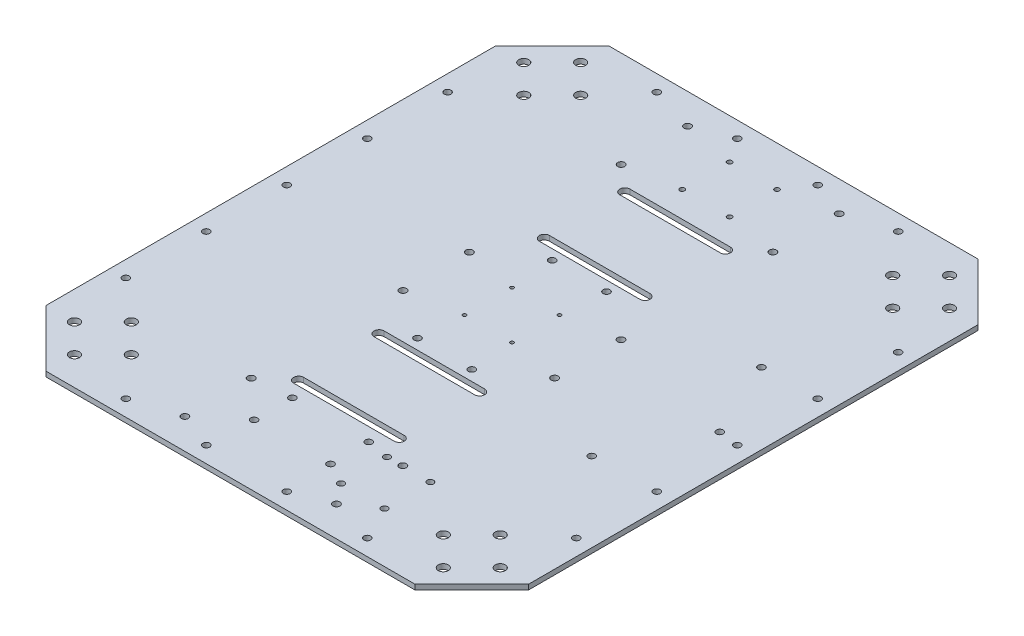
SolidWorks part; units mm, degrees
ref_plane "Front Plane" through (0, 0, 0) normal (0, 0, 1) x (1, 0, 0)
ref_plane "Top Plane" through (0, 0, 0) normal (0, 1, 0) x (1, 0, 0)
ref_plane "Right Plane" through (0, 0, 0) normal (1, 0, 0) x (0, 0, -1)
sketch "Sketch1" plane through (0, 0, 0) normal (0, 1, 0) x (1, 0, 0)
  line L0 (-121.2861, 87.138) -> (-85.365, 123.059)
  line L1 (-121.2861, 123.059) -> (183.5139, 123.059)
  line L2 (-121.2861, 123.059) -> (-121.2861, -232.541)
  line L3 (-121.2861, -232.541) -> (183.5139, -232.541)
  line L4 (183.5139, 123.059) -> (183.5139, -232.541)
  line L5 (31.1139, 95.069) -> (31.1139, -294.9418) construction
  line L6 (-146.0448, -54.741) -> (218.038, -54.741) construction
  line L7 (183.5139, 87.138) -> (147.5929, 123.059)
  line L8 (183.5139, -196.62) -> (147.5929, -232.541)
  line L9 (-121.2861, -196.62) -> (-85.365, -232.541)
  circle A0 centre (-16.7651, 104.009) radius 2.2225
  circle A1 centre (78.9929, 104.009) radius 2.2225
  circle A2 centre (-16.7651, 62.099) radius 2.2225
  circle A3 centre (78.9929, 62.099) radius 2.2225
  circle A4 centre (-16.7651, -171.581) radius 2.2225
  circle A5 centre (78.9929, -171.581) radius 2.2225
  circle A6 centre (78.9929, -213.491) radius 2.2225
  circle A7 centre (-16.7651, -213.491) radius 2.2225
  circle A8 centre (-16.7651, -33.786) radius 2.2225
  circle A9 centre (78.9929, -33.786) radius 2.2225
  circle A10 centre (78.9929, -75.696) radius 2.2225
  circle A11 centre (-16.7651, -75.696) radius 2.2225
  point P8 (31.1139, 123.059)
  point P11 (-121.2861, -54.741)
  dimension "D6" = 95.758
  dimension "D13" = 4.445
  dimension "D1" = 304.8
  dimension "D2" = 355.6
  dimension "D3" = 45
  dimension "D4" = 50.8
  dimension "D5" = 41.91
  dimension "D7" = 104.521
  dimension "D8" = 19.05
  dimension "D9" = 41.91
  dimension "D10" = 20.955
  dimension "D11" = 95.758
  dimension "D12" = 47.879
extrude "Boss-Extrude1" add sketch "Sketch1" along normal blind 3.175
sketch "Sketch2" plane through (0, 3.175, 0) normal (0, 1, 0) x (1, 0, 0)
  line L0 (31.1139, 123.059) -> (31.1139, -287.8465) construction
  line L1 (-85.365, 123.059) -> (147.5929, 123.059) construction
  line L2 (183.5139, -54.741) -> (-158.2106, -54.741) construction
  line L3 (183.5139, 87.138) -> (183.5139, -196.62) construction
  circle A0 centre (13.8419, -12.069) radius 2.159
  circle A1 centre (48.1319, -12.069) radius 2.159
  circle A2 centre (13.8419, -97.159) radius 2.159
  circle A3 centre (48.1319, -97.159) radius 2.159
  dimension "D5" = 4.318
  dimension "D6" = 4.318
  dimension "D7" = 4.318
  dimension "D8" = 4.318
  dimension "D1" = 17.272
  dimension "D2" = 34.29
  dimension "D3" = 85.09
  dimension "D4" = 42.672
extrude "Cut-Extrude1" cut sketch "Sketch2" against normal through all
sketch "Sketch4" plane through (0, 3.175, 0) normal (0, 1, 0) x (1, 0, 0)
  line L0 (-0.6361, 48.256) -> (62.8639, 48.256) construction
  line L1 (-0.6361, 51.431) -> (62.8639, 51.431)
  line L2 (-0.6361, 45.081) -> (62.8639, 45.081)
  line L3 (-0.6361, -2.544) -> (62.8639, -2.544) construction
  line L4 (-0.6361, 0.631) -> (62.8639, 0.631)
  line L5 (-0.6361, -5.719) -> (62.8639, -5.719)
  line L6 (31.1139, 123.059) -> (31.1139, -75.2432) construction
  line L7 (-85.365, 123.059) -> (147.5929, 123.059) construction
  line L8 (-121.2861, -54.741) -> (257.7387, -54.741) construction
  line L9 (-121.2861, 87.138) -> (-121.2861, -196.62) construction
  line L10 (31.1139, -232.541) -> (31.1139, -34.2388) construction
  line L11 (-0.6361, -106.938) -> (62.8639, -106.938) construction
  line L12 (-0.6361, -110.113) -> (62.8639, -110.113)
  line L13 (-0.6361, -103.763) -> (62.8639, -103.763)
  line L14 (-0.6361, -157.738) -> (62.8639, -157.738) construction
  line L15 (-0.6361, -160.913) -> (62.8639, -160.913)
  line L16 (-0.6361, -154.563) -> (62.8639, -154.563)
  arc A0 (-0.6361, 51.431) -> (-0.6361, 45.081) centre (-0.6361, 48.256) ccw
  arc A1 (62.8639, 45.081) -> (62.8639, 51.431) centre (62.8639, 48.256) ccw
  arc A2 (-0.6361, 0.631) -> (-0.6361, -5.719) centre (-0.6361, -2.544) ccw
  arc A3 (62.8639, -5.719) -> (62.8639, 0.631) centre (62.8639, -2.544) ccw
  circle A4 centre (48.1319, -12.069) radius 2.159 construction
  arc A5 (-0.6361, -110.113) -> (-0.6361, -103.763) centre (-0.6361, -106.938) cw
  arc A6 (62.8639, -103.763) -> (62.8639, -110.113) centre (62.8639, -106.938) cw
  arc A7 (-0.6361, -160.913) -> (-0.6361, -154.563) centre (-0.6361, -157.738) cw
  arc A8 (62.8639, -154.563) -> (62.8639, -160.913) centre (62.8639, -157.738) cw
  point P2 (31.1139, 48.256)
  point P7 (31.1139, -2.544)
  point P28 (31.1139, -106.938)
  point P35 (31.1139, -157.738)
  dimension "D1" = 63.5
  dimension "D2" = 63.5
  dimension "D3" = 6.35
  dimension "D4" = 6.35
  dimension "D5" = 44.45
  dimension "D6" = 6.35
extrude "Cut-Extrude2" cut sketch "Sketch4" against normal through all
sketch "Sketch7" plane through (0, 3.175, 0) normal (0, 1, 0) x (1, 0, 0)
  line L0 (31.1139, 123.059) -> (31.1139, -19.2461) construction
  line L3 (-85.365, 123.059) -> (147.5929, 123.059) construction
  circle A0 centre (16.1279, 67.687) radius 1.524
  circle A1 centre (46.0999, 67.687) radius 1.524
  circle A2 centre (16.1279, 97.659) radius 1.524
  circle A3 centre (46.0999, 97.659) radius 1.524
  dimension "D1" = 3.048
  dimension "D2" = 3.048
  dimension "D4" = 14.986
  dimension "D3" = 29.972
  dimension "D5" = 25.4
extrude "Cut-Extrude3" cut sketch "Sketch7" against normal through all
sketch "Sketch8" plane through (0, 3.175, 0) normal (0, 1, 0) x (1, 0, 0)
  line L0 (-85.365, -232.541) -> (147.5929, -232.541) construction
  line L1 (183.5139, 87.138) -> (183.5139, -196.62) construction
  circle A0 centre (73.0239, -207.649) radius 1.524
  circle A1 centre (73.0239, -177.169) radius 1.524
  circle A2 centre (96.8999, -207.649) radius 1.524
  circle A3 centre (96.8999, -177.169) radius 1.524
  dimension "D1" = 3.048
  dimension "D2" = 30.48
  dimension "D3" = 23.876
  dimension "D4" = 24.892
  dimension "D5" = 86.614
extrude "Cut-Extrude4" [suppressed] cut sketch "Sketch8" against normal through all and the other way through all
sketch "Sketch10" plane through (0, 0, 0) normal (0, -1, 0) x (1, 0, 0)
  line L0 (-85.365, 232.541) -> (147.5929, 232.541) construction
  line L1 (31.1139, 232.541) -> (31.1139, 128.7119) construction
  circle A0 centre (6.9839, 193.4758) radius 2.159
  circle A1 centre (55.2439, 193.4758) radius 2.159
  circle A2 centre (6.9839, 169.3458) radius 2.159
  circle A3 centre (55.2439, 169.3458) radius 2.159
  dimension "D1" = 4.318
  dimension "D2" = 48.26
  dimension "D4" = 39.0652
  dimension "D6" = 4.318
  dimension "D7" = 4.318
  dimension "D8" = 4.318
  dimension "D3" = 24.13
  dimension "D5" = 24.13
extrude "Cut-Extrude6" cut sketch "Sketch10" against normal through all
sketch "Sketch9" plane through (0, 0, 0) normal (0, -1, 0) x (-1, 0, 0)
  line L0 (85.365, -232.541) -> (-147.5929, -232.541) construction
  line L1 (121.2861, 87.138) -> (121.2861, -196.62) construction
  line L3 (-147.5929, -232.541) -> (-183.5139, -196.62) construction
  line L4 (-147.5929, -232.541) -> (-111.6719, -196.62) construction
  line L5 (-111.6719, -196.62) -> (-147.5929, -160.699) construction
  line L6 (-183.5139, -196.62) -> (-147.5929, -160.699) construction
  line L8 (-183.5139, -196.62) -> (-147.5929, -232.541) construction
  circle A0 centre (-69.2139, -200.791) radius 2.032
  circle A1 centre (-96.6459, -200.791) radius 2.032
  circle A2 centre (-69.2139, -171.835) radius 2.032
  circle A3 centre (-96.6459, -171.835) radius 2.032
  dimension "D1" = 4.064
  dimension "D2" = 27.432
  dimension "D3" = 28.956
  dimension "D4" = 31.75
  dimension "D5" = 190.5
  dimension "D6" = 50.8
  dimension "D7" = 50.8
extrude "Cut-Extrude5" cut sketch "Sketch9" against normal through all
sketch "Sketch13" plane through (0, 0, 0) normal (0, -1, 0) x (1, 0, 0)
  line L0 (31.1139, -123.059) -> (31.1139, 261.4711) construction
  line L1 (-85.365, -123.059) -> (147.5929, -123.059) construction
  line L2 (-121.2861, 54.741) -> (239.2508, 54.741) construction
  line L3 (-121.2861, -87.138) -> (-121.2861, 196.62) construction
  circle A0 centre (16.1139, 69.741) radius 1.1
  circle A1 centre (16.1139, 39.741) radius 1.1
  circle A2 centre (46.1139, 39.741) radius 1.1
  circle A3 centre (46.1139, 69.741) radius 1.1
  dimension "D1" = 2.2
  dimension "D2" = 2.2
  dimension "D3" = 30
  dimension "D4" = 15
  dimension "D5" = 15
extrude "Cut-Extrude8" cut sketch "Sketch13" against normal through all
sketch "Sketch14" plane through (0, 0, 0) normal (0, -1, 0) x (1, 0, 0)
  line L0 (31.1139, 232.541) -> (31.1139, -154.5354) construction
  line L1 (-85.365, 232.541) -> (147.5929, 232.541) construction
  line L2 (-121.2861, 54.741) -> (331.9066, 54.741) construction
  line L3 (-121.2861, -87.138) -> (-121.2861, 196.62) construction
  line L4 (-85.365, 214.5805) -> (-103.3255, 196.62) construction
  line L5 (-103.3255, 196.62) -> (-85.365, 178.6595) construction
  line L6 (-85.365, 178.6595) -> (-67.4045, 196.62) construction
  line L7 (-67.4045, 196.62) -> (-85.365, 214.5805) construction
  line L8 (-121.2861, 196.62) -> (-85.365, 232.541) construction
  line L9 (-103.3255, 214.5805) -> (-48.3665, 159.6215) construction
  circle A0 centre (-103.3255, 196.62) radius 3.175
  circle A1 centre (-85.365, 214.5805) radius 3.175
  circle A2 centre (-85.365, 178.6595) radius 3.175
  circle A3 centre (-67.4045, 196.62) radius 3.175
  circle A4 centre (129.6324, 196.62) radius 3.175
  circle A5 centre (147.5929, 178.6595) radius 3.175
  circle A6 centre (165.5534, 196.62) radius 3.175
  circle A7 centre (147.5929, 214.5805) radius 3.175
  circle A8 centre (-85.365, -105.0985) radius 3.175
  circle A9 centre (-103.3255, -87.138) radius 3.175
  circle A10 centre (-85.365, -69.1774) radius 3.175
  circle A11 centre (-67.4045, -87.138) radius 3.175
  circle A12 centre (165.5534, -87.138) radius 3.175
  circle A13 centre (147.5929, -69.1774) radius 3.175
  circle A14 centre (147.5929, -105.0985) radius 3.175
  circle A15 centre (129.6324, -87.138) radius 3.175
  dimension "D3" = 6.35
  dimension "D4" = 6.35
  dimension "D5" = 6.35
  dimension "D6" = 6.35
  dimension "D2" = 12.7
  dimension "D7" = 90
  dimension "D8" = 25.4
  dimension "D9" = 25.4
  dimension "D10" = 12.7
  dimension "D11" = 90
extrude "Cut-Extrude9" cut sketch "Sketch14" against normal through all
sketch "Sketch15" plane through (0, 0, 0) normal (0, -1, 0) x (1, 0, 0)
  line L0 (31.1139, 232.541) -> (31.1139, 125.875) construction
  line L1 (-85.365, 232.541) -> (147.5929, 232.541) construction
  line L2 (-121.2861, 54.741) -> (75.4631, 54.741) construction
  line L3 (-121.2861, -87.138) -> (-121.2861, 196.62) construction
  circle A0 centre (5.7139, 222.381) radius 2.159
  circle A1 centre (-45.0861, 222.381) radius 2.159
  circle A2 centre (-111.1261, 54.741) radius 2.159
  circle A3 centre (-111.1261, 105.541) radius 2.159
  circle A4 centre (-111.1261, 156.341) radius 2.159
  circle A5 centre (173.3539, 156.341) radius 2.159
  circle A6 centre (173.3539, 105.541) radius 2.159
  circle A7 centre (173.3539, 54.741) radius 2.159
  circle A8 centre (107.3139, 222.381) radius 2.159
  circle A9 centre (56.5139, 222.381) radius 2.159
  circle A10 centre (56.5139, -112.899) radius 2.159
  circle A11 centre (107.3139, -112.899) radius 2.159
  circle A12 centre (173.3539, 3.941) radius 2.159
  circle A13 centre (173.3539, -46.859) radius 2.159
  circle A14 centre (-111.1261, -46.859) radius 2.159
  circle A15 centre (-111.1261, 3.941) radius 2.159
  circle A16 centre (-45.0861, -112.899) radius 2.159
  circle A17 centre (5.7139, -112.899) radius 2.159
  dimension "D3" = 4.318
  dimension "D4" = 4.318
  dimension "D8" = 4.318
  dimension "D9" = 4.318
  dimension "D10" = 4.318
  dimension "D1" = 25.4
  dimension "D2" = 50.8
  dimension "D5" = 10.16
  dimension "D6" = 50.8
  dimension "D7" = 50.8
  dimension "D11" = 10.16
extrude "Cut-Extrude10" cut sketch "Sketch15" against normal through all
sketch "Sketch16" plane through (0, 0, 0) normal (0, -1, 0) x (-1, 0, 0)
  line L1 (-103.7737, -99.6794) -> (-153.6537, -99.6794)
  line L2 (-103.7737, -99.6794) -> (-103.7737, -11.5294)
  line L3 (-103.7737, -11.5294) -> (-153.6537, -11.5294)
  line L4 (-153.6537, -99.6794) -> (-153.6537, -11.5294)
  line L5 (-183.5139, 87.138) -> (-183.5139, -196.62) construction
  circle A0 centre (-133.3337, -106.6794) radius 2.159
  circle A1 centre (-138.4137, -4.5294) radius 2.159
  circle A2 centre (-160.6539, -53.0294) radius 2.159
  dimension "D3" = 7
  dimension "D4" = 7.0002
  dimension "D5" = 7
  dimension "D6" = 20.32
  dimension "D7" = 15.24
  dimension "D8" = 46.65
  dimension "D9" = 4.318
  dimension "D10" = 4.318
  dimension "D11" = 4.318
  dimension "D1" = 88.15
  dimension "D2" = 49.88
  dimension "D12" = 22.86
extrude "Cut-Extrude11" cut sketch "Sketch16" against normal through all contours A2 | A0 | A1
